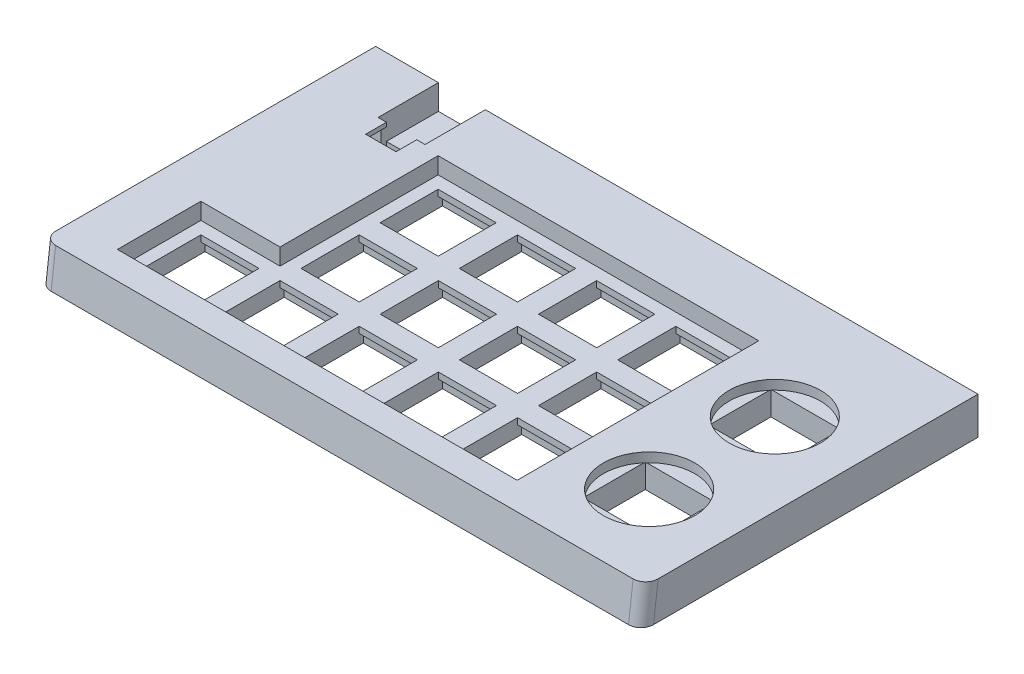
SolidWorks part; units mm, degrees
other "Markup1"
sketch "Sketch7" plane through (-7.5, 4, -73.6318) normal (0, 1, 0) x (1, 0, 0)
other "Markup2"
sketch "Sketch22" plane through (-7.5, 7, -73.8763) normal (-0.114, 0.0781, -0.9904) x (-0.9831, 0.1345, 0.1238)
ref_plane "Front Plane" through (0, 0, 0) normal (0, 0, 1) x (1, 0, 0)
ref_plane "Top Plane" through (0, 0, 0) normal (0, 1, 0) x (1, 0, 0)
ref_plane "Right Plane" through (0, 0, 0) normal (1, 0, 0) x (0, 0, -1)
sketch "Sketch1" plane through (0, 0, 0) normal (0, 1, 0) x (1, 0, 0)
  line L0 (0, 0) -> (6.75, 0)
  line L12 (0, 0) -> (0, 3.55)
  line L17 (20.75, 3.55) -> (25.81, 3.55)
  line L18 (6.75, 3.55) -> (20.75, 3.55)
  line L19 (6.75, 3.55) -> (6.75, 17.55)
  line L24 (6.75, 17.55) -> (20.75, 17.55)
  line L25 (20.75, 3.55) -> (20.75, 17.55)
  line L26 (39.81, 3.55) -> (44.87, 3.55)
  line L27 (25.81, 3.55) -> (39.81, 3.55)
  line L28 (25.81, 3.55) -> (25.81, 17.55)
  line L29 (25.81, 17.55) -> (39.81, 17.55)
  line L30 (39.81, 3.55) -> (39.81, 17.55)
  line L31 (58.87, 3.55) -> (63.93, 3.55)
  line L32 (44.87, 3.55) -> (58.87, 3.55)
  line L33 (44.87, 3.55) -> (44.87, 17.55)
  line L34 (44.87, 17.55) -> (58.87, 17.55)
  line L35 (58.87, 3.55) -> (58.87, 17.55)
  line L36 (77.93, 3.55) -> (82.99, 3.55)
  line L37 (63.93, 3.55) -> (77.93, 3.55)
  line L38 (63.93, 3.55) -> (63.93, 17.55)
  line L39 (63.93, 17.55) -> (77.93, 17.55)
  line L40 (77.93, 3.55) -> (77.93, 17.55)
  line L41 (25.81, 17.55) -> (25.81, 22.6)
  line L42 (82.99, 3.55) -> (96.99, 3.55)
  line L43 (82.99, 3.55) -> (82.99, 17.55)
  line L44 (82.99, 17.55) -> (96.99, 17.55)
  line L45 (96.99, 3.55) -> (96.99, 17.55)
  line L46 (0, 0) -> (130, 0)
  line L51 (0, 0) -> (0, 66.1)
  line L56 (0, 66.1) -> (130, 66.1)
  line L65 (130, 0) -> (130, 66.1)
  line L66 (25.81, 36.6) -> (25.81, 41.65)
  line L67 (25.81, 22.6) -> (39.81, 22.6)
  line L68 (25.81, 22.6) -> (25.81, 36.6)
  line L69 (25.81, 36.6) -> (39.81, 36.6)
  line L70 (39.81, 22.6) -> (39.81, 36.6)
  line L71 (6.75, 17.55) -> (4.23, 17.55)
  line L72 (25.81, 41.65) -> (39.77, 41.65)
  line L73 (25.81, 41.65) -> (25.81, 55.61)
  line L74 (25.81, 55.61) -> (39.77, 55.61)
  line L75 (39.77, 41.65) -> (39.77, 55.61)
  line L76 (44.87, 22.6) -> (58.87, 22.6)
  line L77 (44.87, 22.6) -> (44.87, 36.6)
  line L78 (44.87, 36.6) -> (58.87, 36.6)
  line L79 (58.87, 22.6) -> (58.87, 36.6)
  line L80 (63.93, 22.6) -> (77.93, 22.6)
  line L81 (63.93, 22.6) -> (63.93, 36.6)
  line L82 (63.93, 36.6) -> (77.93, 36.6)
  line L83 (77.93, 22.6) -> (77.93, 36.6)
  line L84 (82.99, 22.6) -> (96.99, 22.6)
  line L85 (82.99, 22.6) -> (82.99, 36.6)
  line L86 (82.99, 36.6) -> (96.99, 36.6)
  line L87 (96.99, 22.6) -> (96.99, 36.6)
  line L88 (44.87, 41.65) -> (58.87, 41.65)
  line L89 (44.87, 41.65) -> (44.87, 55.65)
  line L90 (44.87, 55.65) -> (58.87, 55.65)
  line L91 (58.87, 41.65) -> (58.87, 55.65)
  line L92 (63.93, 41.65) -> (77.93, 41.65)
  line L93 (63.93, 41.65) -> (63.93, 55.65)
  line L94 (63.93, 55.65) -> (77.93, 55.65)
  line L95 (77.93, 41.65) -> (77.93, 55.65)
  line L96 (82.99, 41.65) -> (96.99, 41.65)
  line L97 (82.99, 41.65) -> (82.99, 55.65)
  line L98 (82.99, 55.65) -> (96.99, 55.65)
  line L99 (96.99, 41.65) -> (96.99, 55.65)
  line L100 (4.23, 17.55) -> (4.23, 25.05)
  line L101 (25.81, 55.61) -> (22.06, 55.61)
  line L102 (22.06, 55.61) -> (22.06, 59.415)
  line L103 (96.99, 22.6) -> (109.34, 22.6)
  line L104 (4.23, 25.05) -> (22.06, 25.05)
  line L105 (4.23, 25.05) -> (4.23, 59.415)
  line L106 (4.23, 59.415) -> (22.06, 59.415)
  line L107 (22.06, 25.05) -> (22.06, 59.415)
  line L108 (109.34, 6.985) -> (109.34, 0)
  line L109 (126.14, 21.94) -> (126.14, 37.24)
  line L110 (109.34, 6.985) -> (126.14, 6.985)
  line L111 (109.34, 6.985) -> (109.34, 21.94)
  line L112 (109.34, 21.94) -> (126.14, 21.94)
  line L113 (126.14, 6.985) -> (126.14, 21.94)
  line L114 (126.14, 37.24) -> (126.14, 21.94)
  line L116 (126.14, 37.24) -> (109.34, 37.24)
  line L117 (126.14, 37.24) -> (126.14, 52.195)
  line L118 (126.14, 52.195) -> (109.34, 52.195)
  line L119 (109.34, 37.24) -> (109.34, 52.195)
extrude "Boss-Extrude2" add sketch "Sketch1" along normal blind 4
sketch "Sketch3" plane through (0, 0, 0) normal (0, 1, 0) x (1, 0, 0)
  line L0 (0, 0) -> (6.75, 0)
  line L12 (0, 0) -> (0, 3.55)
  line L18 (6.75, 2.55) -> (20.75, 2.55)
  line L19 (6.75, 2.55) -> (6.75, 18.55)
  line L24 (6.75, 18.55) -> (20.75, 18.55)
  line L25 (20.75, 2.55) -> (20.75, 18.55)
  line L27 (25.81, 2.55) -> (39.81, 2.55)
  line L28 (25.81, 2.55) -> (25.81, 18.55)
  line L29 (25.81, 18.55) -> (39.81, 18.55)
  line L30 (39.81, 2.55) -> (39.81, 18.55)
  line L32 (44.87, 2.55) -> (58.87, 2.55)
  line L33 (44.87, 2.55) -> (44.87, 18.55)
  line L34 (44.87, 18.55) -> (58.87, 18.55)
  line L35 (58.87, 2.55) -> (58.87, 18.55)
  line L36 (25.81, 21.6502) -> (39.81, 21.6502)
  line L37 (63.93, 2.55) -> (77.93, 2.55)
  line L38 (63.93, 2.55) -> (63.93, 18.55)
  line L39 (63.93, 18.55) -> (77.93, 18.55)
  line L40 (77.93, 2.55) -> (77.93, 18.55)
  line L41 (25.81, 21.6502) -> (25.81, 37.6502)
  line L42 (82.99, 2.55) -> (96.99, 2.55)
  line L43 (82.99, 2.55) -> (82.99, 18.55)
  line L44 (82.99, 18.55) -> (96.99, 18.55)
  line L45 (96.99, 2.55) -> (96.99, 18.55)
  line L46 (0, 0) -> (140, 0)
  line L51 (0, 0) -> (0, 66.1)
  line L56 (0, 66.1) -> (140, 66.1)
  line L65 (140, 0) -> (140, 66.1)
  line L66 (25.81, 37.6502) -> (39.81, 37.6502)
  line L71 (39.81, 21.6502) -> (39.81, 37.6502)
  line L100 (25.81, 21.6502) -> (39.81, 37.6502) construction
  line L102 (22.06, 55.65) -> (22.06, 59.415)
  line L103 (25.81, 37.6502) -> (39.81, 21.6502) construction
  line L104 (4.23, 25.09) -> (22.06, 25.09)
  line L105 (4.23, 25.09) -> (4.23, 59.415)
  line L106 (4.23, 59.415) -> (22.06, 59.415)
  line L107 (22.06, 25.09) -> (22.06, 59.415)
  line L108 (109.34, 6.985) -> (109.34, 0)
  line L109 (126.14, 21.94) -> (126.14, 37.24)
  line L110 (109.34, 6.985) -> (126.14, 6.985)
  line L111 (109.34, 6.985) -> (109.34, 21.94)
  line L112 (109.34, 21.94) -> (126.14, 21.94)
  line L113 (126.14, 6.985) -> (126.14, 21.94)
  line L114 (126.14, 37.24) -> (126.14, 21.94)
  line L116 (126.14, 37.24) -> (109.34, 37.24)
  line L117 (126.14, 37.24) -> (126.14, 52.195)
  line L118 (126.14, 52.195) -> (109.34, 52.195)
  line L119 (109.34, 37.24) -> (109.34, 52.195)
  line L125 (25.81, 40.65) -> (39.81, 40.65)
  line L126 (25.81, 40.65) -> (25.81, 56.65)
  line L127 (25.81, 56.65) -> (39.81, 56.65)
  line L128 (39.81, 40.65) -> (39.81, 56.65)
  line L129 (25.81, 40.65) -> (39.81, 56.65) construction
  line L130 (25.81, 56.65) -> (39.81, 40.65) construction
  line L131 (44.87, 40.65) -> (58.87, 40.65)
  line L132 (44.87, 40.65) -> (44.87, 56.65)
  line L133 (44.87, 56.65) -> (58.87, 56.65)
  line L134 (58.87, 40.65) -> (58.87, 56.65)
  line L135 (44.87, 40.65) -> (58.87, 56.65) construction
  line L136 (44.87, 56.65) -> (58.87, 40.65) construction
  line L137 (63.93, 40.65) -> (77.93, 40.65)
  line L138 (63.93, 40.65) -> (63.93, 56.65)
  line L139 (63.93, 56.65) -> (77.93, 56.65)
  line L140 (77.93, 40.65) -> (77.93, 56.65)
  line L141 (63.93, 40.65) -> (77.93, 56.65) construction
  line L142 (63.93, 56.65) -> (77.93, 40.65) construction
  line L143 (82.99, 40.65) -> (96.99, 40.65)
  line L144 (82.99, 40.65) -> (82.99, 56.65)
  line L145 (82.99, 56.65) -> (96.99, 56.65)
  line L146 (96.99, 40.65) -> (96.99, 56.65)
  line L147 (82.99, 40.65) -> (96.99, 56.65) construction
  line L148 (82.99, 56.65) -> (96.99, 40.65) construction
  line L149 (82.99, 21.6) -> (96.99, 21.6)
  line L150 (82.99, 21.6) -> (82.99, 37.6)
  line L151 (82.99, 37.6) -> (96.99, 37.6)
  line L152 (96.99, 21.6) -> (96.99, 37.6)
  line L153 (82.99, 21.6) -> (96.99, 37.6) construction
  line L154 (82.99, 37.6) -> (96.99, 21.6) construction
  line L155 (63.93, 21.6) -> (77.93, 21.6)
  line L156 (63.93, 21.6) -> (63.93, 37.6)
  line L157 (63.93, 37.6) -> (77.93, 37.6)
  line L158 (77.93, 21.6) -> (77.93, 37.6)
  line L159 (63.93, 21.6) -> (77.93, 37.6) construction
  line L160 (63.93, 37.6) -> (77.93, 21.6) construction
  line L161 (44.87, 21.6) -> (58.87, 21.6)
  line L162 (44.87, 21.6) -> (44.87, 37.6)
  line L163 (44.87, 37.6) -> (58.87, 37.6)
  line L164 (58.87, 21.6) -> (58.87, 37.6)
  line L165 (44.87, 21.6) -> (58.87, 37.6) construction
  line L166 (44.87, 37.6) -> (58.87, 21.6) construction
  point P26 (32.81, 29.6502)
  point P30 (32.81, 48.65)
  point P36 (51.87, 48.65)
  point P41 (70.93, 48.65)
  point P46 (89.99, 48.65)
  point P51 (89.99, 29.6)
  point P56 (70.93, 29.6)
  point P93 (51.87, 29.6)
extrude "Cut-Extrude1" cut sketch "Sketch3" along normal blind 2.5 contours L149 L152 L151 L150 | L157 L158 L155 L156 | L145 L146 L143 L144 | L139 L140 L137 L138 | L133 L134 L131 L132 | L127 L128 L125 L126 | L66 L71 L36 L41 | L163 L164 L161 L162 | L24 L25 L18 L19 | L29 L30 L27 L28 | L34 L35 L32 L33 | L39 L40 L37 L38 | L44 L45 L42 L43
ref_plane "Plane1" through (0, 0, 0) normal (0, -1, 0) x (-1, 0, 0)
sketch "Sketch5" plane through (0, 0, 0) normal (0, -1, 0) x (-1, 0, 0)
  line L1 (0, 0) -> (-2.25, 0)
  line L2 (0, 0) -> (0, 2.25)
  line L3 (0, 2.25) -> (-2.25, 2.25)
  line L4 (-2.25, 0) -> (-2.25, 2.25)
  line L5 (0, 66.1) -> (-2.25, 66.1)
  line L6 (0, 66.1) -> (0, 63.85)
  line L7 (0, 63.85) -> (-2.25, 63.85)
  line L8 (-2.25, 66.1) -> (-2.25, 63.85)
  line L9 (-130, 66.1) -> (-127.75, 66.1)
  line L10 (-130, 66.1) -> (-130, 63.85)
  line L11 (-130, 63.85) -> (-127.75, 63.85)
  line L12 (-127.75, 66.1) -> (-127.75, 63.85)
  line L13 (-130, 0) -> (-127.75, 0)
  line L14 (-130, 0) -> (-130, 2.25)
  line L15 (-130, 2.25) -> (-127.75, 2.25)
  line L16 (-127.75, 0) -> (-127.75, 2.25)
  circle A0 centre (-2.25, 2.25) radius 1.25
  circle A1 centre (-2.25, 63.85) radius 1.25
  circle A2 centre (-127.75, 63.85) radius 1.25
  circle A3 centre (-127.75, 2.25) radius 1.25
sketch "Sketch6" plane through (0, 0, 0) normal (0, -1, 0) x (-1, 0, 0)
  line L0 (-2.25, 2.25) -> (7.5, 2.25)
  line L1 (7.5, 2.25) -> (7.5, -7.2482)
  line L2 (-6.75, 12.4964) -> (-3.75, 12.4964)
  line L3 (7.5, -7.2482) -> (-137.5, -7.2482)
  line L4 (7.5, -7.2482) -> (7.5, 73.8763)
  line L5 (7.5, 73.8763) -> (-137.5, 73.8763)
  line L6 (-137.5, -7.2482) -> (-137.5, 73.8763)
  line L11 (-6.75, 3.55) -> (-6.75, 17.55) construction
  line L12 (-20.75, 17.55) -> (-20.75, 20.55)
  line L13 (-99.99, 58.61) -> (-39.77, 58.61)
  line L14 (-25.81, 41.65) -> (-22.81, 41.65)
  line L15 (-20.75, 3.55) -> (-20.75, 0.4618)
  line L16 (-20.75, 0.4618) -> (-99.99, 0.4618)
  line L17 (-20.75, 0.4618) -> (-3.75, 0.4618)
  line L18 (-3.75, 0.4618) -> (-3.75, 12.4964)
  line L19 (-3.75, 12.4964) -> (-3.75, 20.55)
  line L20 (-3.75, 20.55) -> (-22.81, 20.55)
  line L21 (-22.81, 20.55) -> (-22.81, 53.2223)
  line L22 (-39.77, 55.61) -> (-39.77, 58.61)
  line L23 (-39.77, 58.61) -> (-22.81, 58.61)
  line L24 (-22.81, 58.61) -> (-22.81, 53.2223)
  line L27 (-96.99, 17.55) -> (-99.99, 17.55)
  line L29 (-99.99, 0.4618) -> (-99.99, 58.61)
  dimension "D1" = 145
  dimension "D2" = 81.1245
extrude "Boss-Extrude3" add sketch "Sketch6" against normal blind 8
ref_plane "Plane2" through (0, 4, 0) normal (0, -1, 0) x (-1, 0, 0)
ref_plane "Plane3" through (0, 1, 0) normal (0, -1, 0) x (-1, 0, 0)
sketch "Sketch12" plane through (0, 0, 0) normal (0, -1, 0) x (-1, 0, 0)
  line L1 (0, 0) -> (-2.25, 0)
  line L2 (0, 0) -> (0, 2.25)
  line L3 (0, 2.25) -> (-2.25, 2.25)
  line L4 (-2.25, 0) -> (-2.25, 2.25)
  line L5 (0, 66.1) -> (-2.25, 66.1)
  line L6 (0, 66.1) -> (0, 63.85)
  line L7 (0, 63.85) -> (-2.25, 63.85)
  line L8 (-2.25, 66.1) -> (-2.25, 63.85)
  line L9 (-130, 66.0692) -> (-127.75, 66.0692)
  line L10 (-130, 66.0692) -> (-130, 63.8192)
  line L11 (-130, 63.8192) -> (-127.75, 63.8192)
  line L12 (-127.75, 66.0692) -> (-127.75, 63.8192)
  line L13 (-130, 0) -> (-127.75, 0)
  line L14 (-130, 0) -> (-130, 2.25)
  line L15 (-130, 2.25) -> (-127.75, 2.25)
  line L16 (-127.75, 0) -> (-127.75, 2.25)
  circle A0 centre (-2.25, 2.25) radius 1.25
  circle A1 centre (-2.25, 63.85) radius 1.25
  circle A2 centre (-127.75, 63.8192) radius 1.25
  circle A3 centre (-127.75, 2.25) radius 1.25
extrude "Cut-Extrude5" cut sketch "Sketch12" against normal blind 6 contours L8 A1 L7 | L7 A1 L8 | L3 A0 L4 | L4 A0 L3 | L16 A3 L15 | L15 A3 L16 | A2
sketch "Sketch13" plane through (0, 0, 0) normal (0, -1, 0) x (1, 0, 0)
  line L17 (22.7, -25.05) -> (3.77, -25.05)
  line L18 (22.7, -25.05) -> (22.7, -60.05)
  line L19 (22.7, -60.05) -> (3.77, -60.05)
  line L20 (3.77, -25.05) -> (3.77, -60.05)
extrude "Cut-Extrude6" cut sketch "Sketch13" against normal blind 7
sketch "Sketch14" plane through (0, 0, 0) normal (0, -1, 0) x (1, 0, 0)
  line L0 (126.14, -14.4625) -> (117.74, -14.4625)
  line L9 (126.14, -44.7175) -> (117.74, -44.7175)
  line L11 (109.34, -6.985) -> (126.14, -6.985)
  line L12 (109.34, -6.985) -> (109.34, -21.94)
  line L13 (109.34, -21.94) -> (126.14, -21.94)
  line L14 (126.14, -6.985) -> (126.14, -21.94)
  line L15 (109.34, -6.985) -> (126.14, -21.94) construction
  line L16 (109.34, -21.94) -> (126.14, -6.985) construction
  line L17 (109.34, -37.24) -> (126.14, -37.24)
  line L18 (109.34, -37.24) -> (109.34, -52.195)
  line L19 (109.34, -52.195) -> (126.14, -52.195)
  line L20 (126.14, -37.24) -> (126.14, -52.195)
  line L21 (109.34, -37.24) -> (126.14, -52.195) construction
  line L22 (109.34, -52.195) -> (126.14, -37.24) construction
sketch "Sketch15" plane through (0, 0, 0) normal (0, -1, 0) x (1, 0, 0)
  circle A0 centre (117.74, -44.7175) radius 4
  circle A1 centre (117.74, -14.4625) radius 4
extrude "Cut-Extrude8" cut sketch "Sketch14" against normal blind 5.75
extrude "Cut-Extrude9" cut sketch "Sketch15" against normal blind 10
ref_plane "Plane4" through (0, 8, 0) normal (0, 1, 0) x (1, 0, 0)
sketch "Sketch16" plane through (0, 8, 0) normal (0, 1, 0) x (1, 0, 0)
  circle A0 centre (117.74, 44.7175) radius 11
  circle A1 centre (117.74, 14.4625) radius 11
extrude "Cut-Extrude10" cut sketch "Sketch16" against normal blind 2.25
sketch "Sketch20" plane through (0, 0, 0) normal (0, -1, 0) x (1, 0, 0)
  line L1 (-7.5, -73.8763) -> (137.5, -73.8763)
  line L2 (-7.5, -73.8763) -> (-7.5, 7.2482)
  line L3 (-7.5, 7.2482) -> (137.5, 7.2482)
  line L4 (137.5, -73.8763) -> (137.5, 7.2482)
  line L5 (0, -66.1) -> (130, -66.1)
  line L6 (0, -66.1) -> (0, 0)
  line L7 (0, 0) -> (130, 0)
  line L8 (130, -66.1) -> (130, 0)
extrude "Boss-Extrude5" add sketch "Sketch20" along normal blind 1
ref_plane "Plane5" through (0, -1.8619, 0.2286) normal (0, 0.9925, -0.1219) x (-1, 0, 0)
sketch "Sketch21" plane through (0, -1.8619, 0.2286) normal (0, 0.9925, -0.1219) x (-1, 0, 0)
  line L1 (7.5, 7.0723) -> (-137.5, 7.0723)
  line L2 (7.5, 7.0723) -> (7.5, 41.9391)
  line L3 (7.5, 41.9391) -> (-137.5, 41.9391)
  line L4 (-137.5, 7.0723) -> (-137.5, 41.9391)
extrude "Cut-Extrude11" cut sketch "Sketch21" along normal blind 18
fillet "Fillet1" radius 3 2 edges at (137.5, 3.5, 6.6957) (-7.5, 3.5, 6.6957)
sketch "Sketch28" plane through (0, 0, 0) normal (0, -1, 0) x (1, 0, 0)
  line L0 (25.81, -55.61) -> (16.91, -55.61)
  line L1 (16.91, -55.61) -> (16.91, -54.36)
  line L2 (16.91, -59.36) -> (18.91, -59.36)
  line L3 (16.91, -54.36) -> (9.61, -54.36)
  line L4 (16.91, -54.36) -> (16.91, -59.36)
  line L5 (16.91, -59.36) -> (9.61, -59.36)
  line L6 (9.61, -54.36) -> (9.61, -59.36)
  line L7 (9.61, -59.36) -> (7.61, -59.36)
  line L14 (7.61, -59.36) -> (18.91, -59.36)
  line L15 (7.61, -59.36) -> (7.61, -61.36)
  line L16 (7.61, -61.36) -> (18.91, -61.36)
  line L17 (18.91, -59.36) -> (18.91, -61.36)
extrude "Cut-Extrude14" cut sketch "Sketch28" against normal blind 10 contours L3 L6 L5 L4 L1 | L14 L15 L16 L17
sketch "Sketch31" plane through (0, 0, -61.36) normal (0, 0, 1) x (1, 0, 0)
  line L0 (18.91, 8) -> (18.91, 0) construction
  line L1 (7.61, 8) -> (18.91, 8)
  line L2 (7.61, 8) -> (7.61, 2)
  line L3 (7.61, 2) -> (18.91, 2)
  line L4 (18.91, 8) -> (18.91, 2)
extrude "Cut-Extrude15" cut sketch "Sketch31" against normal blind 16
